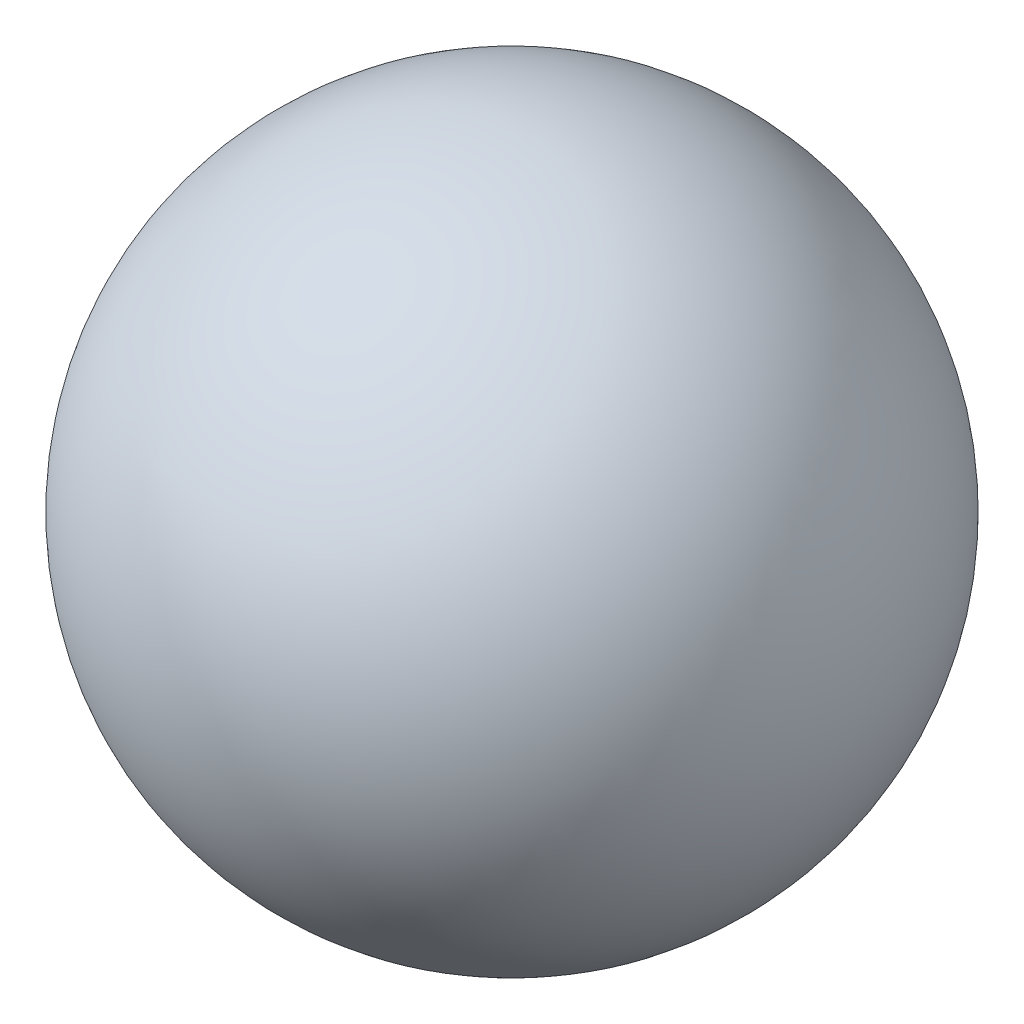
SolidWorks part; units mm, degrees
ref_plane "Front Plane" through (0, 0, 0) normal (0, 0, 1) x (1, 0, 0)
ref_plane "Top Plane" through (0, 0, 0) normal (0, 1, 0) x (1, 0, 0)
ref_plane "Right Plane" through (0, 0, 0) normal (1, 0, 0) x (0, 0, -1)
sketch "Sketch1" plane through (0, 0, 0) normal (1, 0, 0) x (0, 0, -1)
  line L0 (0, 25) -> (0, -25) construction
  line L1 (0, 25) -> (0, -25)
  arc A0 (0, -25) -> (0, 25) centre (0, 0) ccw
  dimension "D1" = 50
revolve "Revolve3" add sketch "Sketch1" angle 360 about L0
